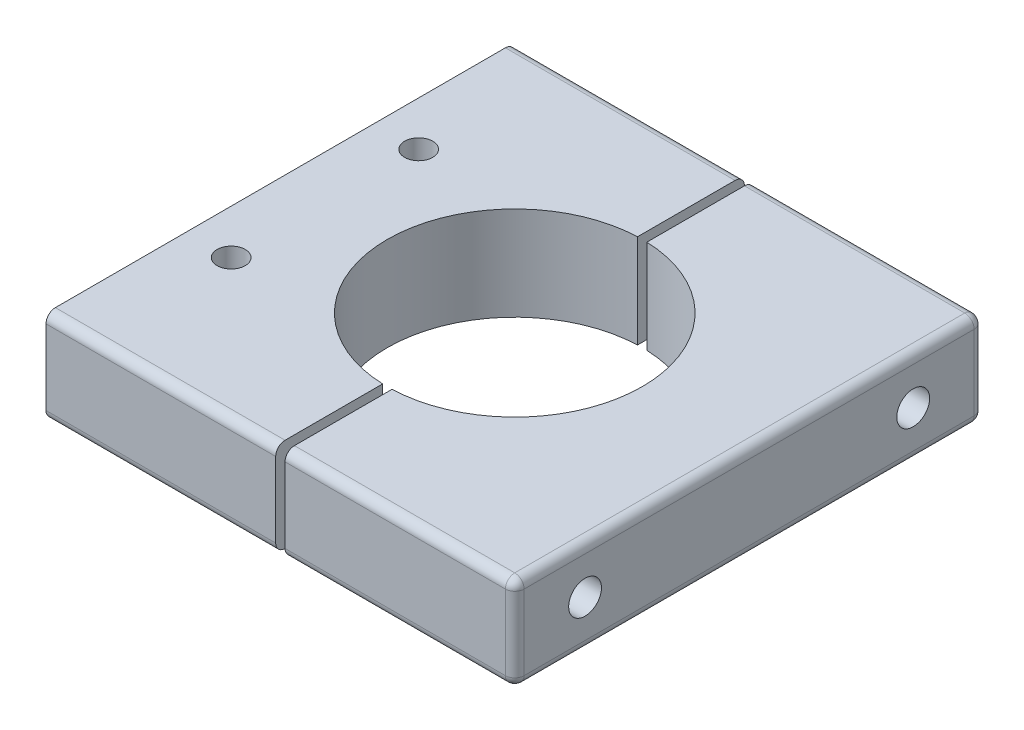
SolidWorks part; units mm, degrees
ref_plane "Front Plane" through (0, 0, 0) normal (0, 0, 1) x (1, 0, 0)
ref_plane "Top Plane" through (0, 0, 0) normal (0, 1, 0) x (1, 0, 0)
ref_plane "Right Plane" through (0, 0, 0) normal (1, 0, 0) x (0, 0, -1)
ref_plane "Plan1" through (0, 0, 0) normal (1, 0, 0) x (0, 0, -1)
sketch "Esquisse1" plane through (0, 0, 0) normal (0, 1, 0) x (1, 0, 0)
  line L0 (1, 47.7167) -> (50, 47.7167)
  line L1 (50, 47.7167) -> (50, -52.2833)
  line L2 (50, -52.2833) -> (1, -52.2833)
  line L3 (1, -52.2833) -> (1, 47.7167)
  line L4 (0, -55) -> (0, 55) construction
  dimension "D1" = 1
  dimension "D2" = 49
  dimension "D3" = 100
extrude "Boss.-Extru.1" add sketch "Esquisse1" along normal blind 20
sketch "Esquisse2" plane through (0, 0, 0) normal (0, 1, 0) x (1, 0, 0)
  line L0 (-1, 47.7167) -> (-1, -52.2833)
  line L1 (-1, -52.2833) -> (-50, -52.2833)
  line L2 (-50, -52.2833) -> (-50, 47.7167)
  line L3 (-50, 47.7167) -> (-1, 47.7167)
  line L4 (0, -11) -> (0, 11) construction
  line L5 (50, 47.7167) -> (1, 47.7167) construction
  dimension "D1" = 49
  dimension "D2" = 100
  dimension "D3" = 1
extrude "Boss.-Extru.2" add sketch "Esquisse2" along normal blind 20 separate body
sketch "Esquisse3" plane through (0, 20, 0) normal (0, 1, 0) x (1, 0, 0)
  line L0 (50, -2.2833) -> (-50, -2.2833) construction
  line L1 (50, -52.2833) -> (50, 47.7167) construction
  line L2 (-50, 47.7167) -> (-50, -52.2833) construction
  circle A0 centre (0, -2.2833) radius 27.2
extrude "Enlèv. mat.-Extru.1" cut sketch "Esquisse3" against normal through all
sketch "Esquisse4" plane through (-50, 0, 0) normal (-1, 0, 0) x (0, 0, 1)
  line L0 (-47.7167, 10) -> (52.2833, 10) construction
  line L1 (-47.7167, 20) -> (-47.7167, 0) construction
  line L2 (52.2833, 20) -> (52.2833, 0) construction
  circle A0 centre (-32.7167, 10) radius 3.5
  circle A1 centre (37.2833, 10) radius 3.5
  point P10 (2.2833, 10)
  dimension "D1" = 35
  dimension "D2" = 35
extrude "Enlèv. mat.-Extru.2" cut sketch "Esquisse4" against normal through all
sketch "Esquisse5" plane through (0, 20, 0) normal (0, 1, 0) x (1, 0, 0)
  line L0 (-50, -2.2833) -> (50, -2.2833) construction
  line L1 (-50, 47.7167) -> (-50, -52.2833) construction
  line L2 (50, -52.2833) -> (50, 47.7167) construction
  circle A0 centre (-40.5, 17.7167) radius 3
  circle A1 centre (-40.5, -22.2833) radius 3
  point P12 (-46.2408, -21.985)
  point P13 (-40.4001, -21.7646)
  dimension "D1" = 9.5
  dimension "D3" = 20
  dimension "D2" = 20
  dimension "D4" = 9.5
extrude "Enlèv. mat.-Extru.3" cut sketch "Esquisse5" against normal through all
sketch "Esquisse7" plane through (-50, 0, 0) normal (-1, 0, 0) x (0, 0, 1)
  line L0 (-36.2167, 10) -> (-29.2167, 10) construction
  line L1 (-32.7167, 13.5) -> (-32.7167, 6.5) construction
  line L2 (37.2833, 13.5) -> (37.2833, 6.5) construction
  line L3 (33.7833, 10) -> (40.7833, 10) construction
  line L5 (-26.9644, 6.922) -> (-27.1749, 13.4426)
  line L6 (-27.1749, 13.4426) -> (-32.9272, 16.5207)
  line L7 (-32.9272, 16.5207) -> (-38.469, 13.078)
  line L8 (-38.469, 13.078) -> (-38.2585, 6.5574)
  line L9 (-38.2585, 6.5574) -> (-32.5062, 3.4793)
  line L10 (-32.5062, 3.4793) -> (-26.9644, 6.922)
  line L11 (37.2833, 3.4759) -> (42.9333, 6.738)
  line L12 (42.9333, 6.738) -> (42.9333, 13.262)
  line L13 (42.9333, 13.262) -> (37.2833, 16.5241)
  line L14 (37.2833, 16.5241) -> (31.6333, 13.262)
  line L15 (31.6333, 13.262) -> (31.6333, 6.738)
  line L16 (31.6333, 6.738) -> (37.2833, 3.4759)
  circle A0 centre (-32.7167, 10) radius 3.5 construction
  circle A1 centre (37.2833, 10) radius 3.5 construction
  circle A2 centre (-32.7167, 10) radius 5.65 construction
  circle A3 centre (37.2833, 10) radius 5.65 construction
extrude "Enlèv. mat.-Extru.5" cut sketch "Esquisse7" against normal blind 5
fillet "Congé1" radius 2 4 edges at (-25.5, 0, -47.7167) (-25.5, 0, 52.2833) (-25.5, 20, 52.2833) (-25.5, 20, -47.7167)
fillet "Congé2" radius 2 8 edges at (25.5, 0, -47.7167) (50, 10, -47.7167) (50, 0, 2.2833) (50, 10, 52.2833) (25.5, 0, 52.2833) (25.5, 20, 52.2833) (50, 20, 2.2833) (25.5, 20, -47.7167)
